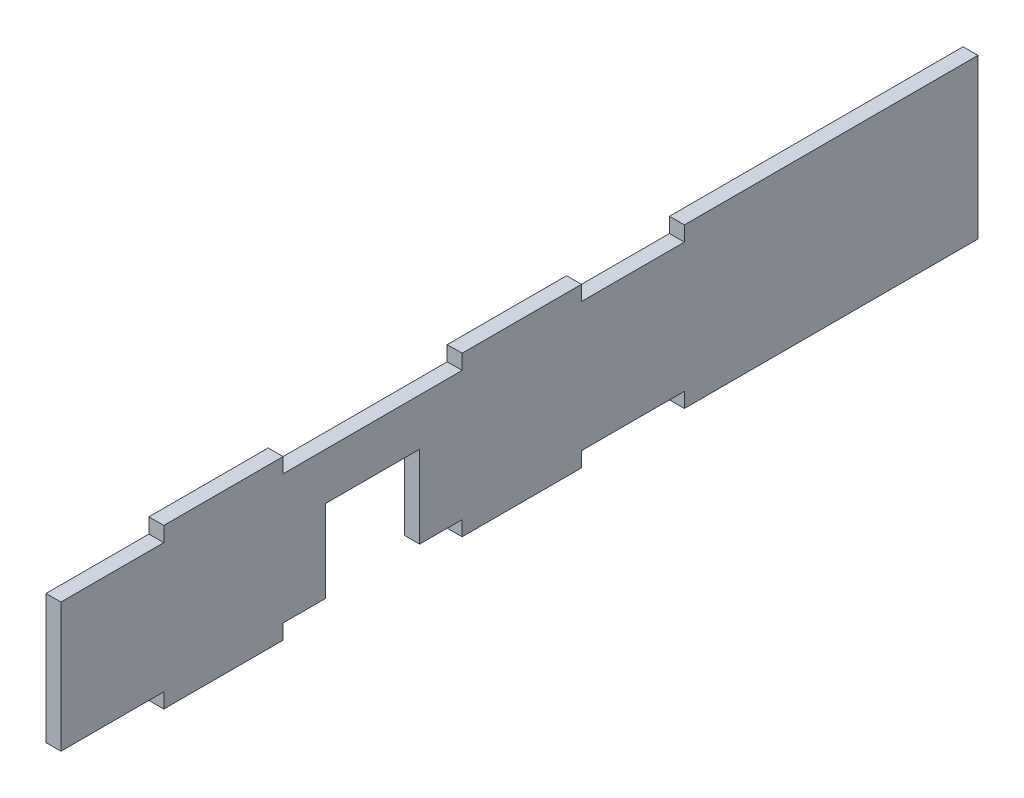
SolidWorks part; units mm, degrees
material "Acrylic (Medium-high impact)"
ref_plane "Front Plane" through (0, 0, 0) normal (0, 0, 1) x (1, 0, 0)
ref_plane "Top Plane" through (0, 0, 0) normal (0, 1, 0) x (1, 0, 0)
ref_plane "Right Plane" through (0, 0, 0) normal (1, 0, 0) x (0, 0, -1)
sketch "Sketch2" plane through (0, 0, 0) normal (0, 1, 0) x (1, 0, 0)
  line L0 (-147.5, 0) -> (147.5, 0) construction
  line L5 (-185, 195.2) -> (185, 195.2) construction
  line L6 (-197.7, -132.7) -> (197.7, -132.7)
  line L13 (110, 120) -> (185, 120)
  line L14 (110, 120) -> (110, -120)
  line L15 (110, -120) -> (185, -120)
  line L16 (185, 120) -> (185, -120)
  line L17 (110, 120) -> (185, -120) construction
  line L18 (110, -120) -> (185, 120) construction
  line L19 (-185, 120) -> (-110, 120)
  line L20 (-185, 120) -> (-185, -120)
  line L21 (-185, -120) -> (-110, -120)
  line L22 (-110, 120) -> (-110, -120)
  line L23 (-185, 120) -> (-110, -120) construction
  line L24 (-185, -120) -> (-110, 120) construction
  line L26 (-110, -37.5) -> (110, -37.5)
  line L27 (-110, -37.5) -> (-110, 37.5)
  line L28 (-110, 37.5) -> (110, 37.5)
  line L29 (110, -37.5) -> (110, 37.5)
  line L30 (-110, -37.5) -> (110, 37.5) construction
  line L31 (-110, 37.5) -> (110, -37.5) construction
  line L41 (-197.7, -132.7) -> (-197.7, 132.7)
  line L42 (-185, 132.7) -> (185, 132.7) construction
  line L43 (197.7, -132.7) -> (197.7, 132.7)
  line L44 (-197.7, -132.7) -> (197.7, 132.7) construction
  line L45 (-197.7, 132.7) -> (197.7, -132.7) construction
  line L47 (-197.7, 132.7) -> (-197.7, 257.7)
  line L48 (-197.7, 257.7) -> (-185, 257.7)
  line L49 (-185, 132.7) -> (-185, 257.7)
  line L51 (185, 132.7) -> (185, 257.7)
  line L52 (185, 257.7) -> (197.7, 257.7)
  line L53 (197.7, 132.7) -> (197.7, 257.7)
  line L54 (-185, 132.7) -> (185, 132.7)
  line L55 (223.1, 132.7) -> (223.1, 283.1)
  line L56 (159.6, 283.1) -> (223.1, 283.1)
  line L57 (159.6, 158.1) -> (159.6, 283.1)
  line L58 (-159.6, 158.1) -> (159.6, 158.1)
  line L59 (-159.6, 158.1) -> (-159.6, 283.1)
  line L60 (-223.1, 283.1) -> (-159.6, 283.1)
  line L61 (-223.1, 132.7) -> (-223.1, 283.1)
  line L62 (-223.1, -158.1) -> (-223.1, 132.7)
  line L63 (-223.1, -158.1) -> (223.1, -158.1)
  line L64 (223.1, -158.1) -> (223.1, 132.7)
  circle A0 centre (0, 308.1) radius 150
  point P2 (0, 0)
  point P13 (147.5, 0)
  point P18 (-147.5, 0)
  point P23 (0, 0)
  point P24 (0, 0)
  point P35 (0, 195.2)
  dimension "D1" = 300
  dimension "D2" = 75
  dimension "D3" = 240
  dimension "D4" = 75
  dimension "D5" = 220
  dimension "D6" = 12.7
  dimension "D7" = 12.7
  dimension "D8" = 12.7
  dimension "D9" = 125
  dimension "D10" = 25.4
sketch "Sketch3" plane through (0, 0, 0) normal (1, 0, 0) x (0, 0, -1)
  line L1 (-132.7, 0) -> (257.7, 0)
  line L2 (-132.7, 0) -> (-132.7, 55)
  line L3 (-132.7, 55) -> (257.7, 55)
  line L4 (257.7, 0) -> (257.7, 55)
  line L5 (-20, -35) -> (20, -35)
  line L6 (-20, -35) -> (-20, 35)
  line L7 (-20, 35) -> (20, 35)
  line L8 (20, -35) -> (20, 35)
  line L9 (-20, -35) -> (20, 35) construction
  line L10 (-20, 35) -> (20, -35) construction
  point P7 (0, 0)
  dimension "D1" = 55
  dimension "D2" = 40
  dimension "D3" = 70
extrude "Boss-Extrude1" add sketch "Sketch3" along normal blind 6.35 contours L8 L1 L4 L3 L2 L6 L7
sketch "Sketch4" plane through (0, 0, 0) normal (0, -1, 0) x (1, 0, 0)
  line L0 (0, -20) -> (0, -257.7) construction
  line L1 (0, -257.7) -> (6.35, -257.7) construction
  line L2 (6.35, -257.7) -> (6.35, -20) construction
  line L3 (6.35, -20) -> (0, -20) construction
  line L4 (0, 132.7) -> (0, 20) construction
  line L5 (0, 20) -> (6.35, 20) construction
  line L6 (6.35, 20) -> (6.35, 132.7) construction
  line L7 (6.35, 132.7) -> (0, 132.7) construction
  line L8 (0, -20) -> (0, -257.7)
  line L9 (0, -257.7) -> (6.35, -257.7)
  line L10 (6.35, -257.7) -> (6.35, -20)
  line L11 (6.35, -20) -> (0, -20)
  line L12 (0, 132.7) -> (0, 20)
  line L13 (0, 20) -> (6.35, 20)
  line L14 (6.35, 20) -> (6.35, 132.7)
  line L15 (6.35, 132.7) -> (0, 132.7)
extrude "Boss-Extrude2" add sketch "Sketch4" along normal blind 6.35
sketch "Sketch5" plane through (0, 55, 0) normal (0, 1, 0) x (1, 0, 0)
  line L4 (0, 257.7) -> (0, -132.7)
  line L5 (0, -132.7) -> (6.35, -132.7)
  line L6 (6.35, -132.7) -> (6.35, 257.7)
  line L7 (6.35, 257.7) -> (0, 257.7)
  line L8 (0, 257.7) -> (0, -132.7)
  line L9 (0, -132.7) -> (6.35, -132.7)
  line L10 (6.35, -132.7) -> (6.35, 257.7)
  line L11 (6.35, 257.7) -> (0, 257.7)
  dimension "D1" = 0
extrude "Boss-Extrude3" add sketch "Sketch5" along normal blind 6.35
sketch "Sketch6" plane through (6.35, 0, 0) normal (1, 0, 0) x (0, 0, -1)
  line L0 (-126.35, 55) -> (-126.35, 0)
  line L1 (-126.35, 0) -> (-26.35, 0)
  line L2 (-26.35, 0) -> (-26.35, 41.35)
  line L3 (-26.35, 41.35) -> (26.35, 41.35)
  line L4 (26.35, 41.35) -> (26.35, 0)
  line L5 (26.35, 0) -> (251.35, 0)
  line L6 (251.35, 0) -> (251.35, 55)
  line L7 (251.35, 55) -> (-126.35, 55)
  line L8 (20, 35) -> (20, -6.35)
  line L9 (20, -6.35) -> (257.7, -6.35)
  line L10 (257.7, -6.35) -> (257.7, 61.35)
  line L11 (257.7, 61.35) -> (-132.7, 61.35)
  line L12 (-132.7, 61.35) -> (-132.7, -6.35)
  line L13 (-132.7, -6.35) -> (-20, -6.35)
  line L14 (-20, -6.35) -> (-20, 35)
  line L15 (-20, 35) -> (20, 35)
  line L16 (20, 35) -> (20, -6.35)
  line L17 (20, -6.35) -> (257.7, -6.35)
  line L18 (257.7, -6.35) -> (257.7, 61.35)
  line L19 (257.7, 61.35) -> (-132.7, 61.35)
  line L20 (-132.7, 61.35) -> (-132.7, -6.35)
  line L21 (-132.7, -6.35) -> (-20, -6.35)
  line L22 (-20, -6.35) -> (-20, 35)
  line L23 (-20, 35) -> (20, 35)
  line L24 (-132.7, 0) -> (257.7, 0)
  line L25 (-132.7, 55) -> (257.7, 55)
  line L26 (132.7, 0) -> (132.7, -6.35)
  line L27 (-88.9, 0) -> (-38.1, 0)
  line L28 (-88.9, 0) -> (-88.9, -6.35)
  line L29 (-88.9, -6.35) -> (-38.1, -6.35)
  line L30 (-38.1, 0) -> (-38.1, -6.35)
  line L31 (38.1, 0) -> (88.9, 0)
  line L32 (38.1, 0) -> (38.1, -6.35)
  line L33 (38.1, -6.35) -> (88.9, -6.35)
  line L34 (88.9, 0) -> (88.9, -6.35)
  line L35 (-132.7, 27.5) -> (257.7, 27.5) construction
  line L36 (132.7, 55) -> (132.7, 61.35)
  line L37 (88.9, 55) -> (88.9, 61.35)
  line L38 (38.1, 55) -> (38.1, 61.35)
  line L39 (-38.1, 55) -> (-38.1, 61.35)
  line L40 (-88.9, 55) -> (-88.9, 61.35)
  line M14 (20, -6.35) -> (257.7, -6.35)
  line M17 (-132.7, 61.35) -> (-132.7, -6.35)
  line M18 (-132.7, -6.35) -> (-20, -6.35)
  line M19 (-20, -6.35) -> (-20, 35)
  dimension "D3" = 50.8
  dimension "D4" = 50.8
  dimension "D5" = 76.2
  dimension "D6" = 38.1
  dimension "D7" = 132.7
  dimension "D1" = 0
  dimension "D2" = 6.35
extrude "Cut-Extrude1" cut sketch "Sketch6" against normal through all contours L25 L40 L19 M17 | L28 L1 L24 L20 M18 | L39 L25 L38 L19 | L32 L5 L24 L16 M14 | L1 L30 L24 M18 M19 | L37 L25 L36 L19 | L5 L34 L26 M14
